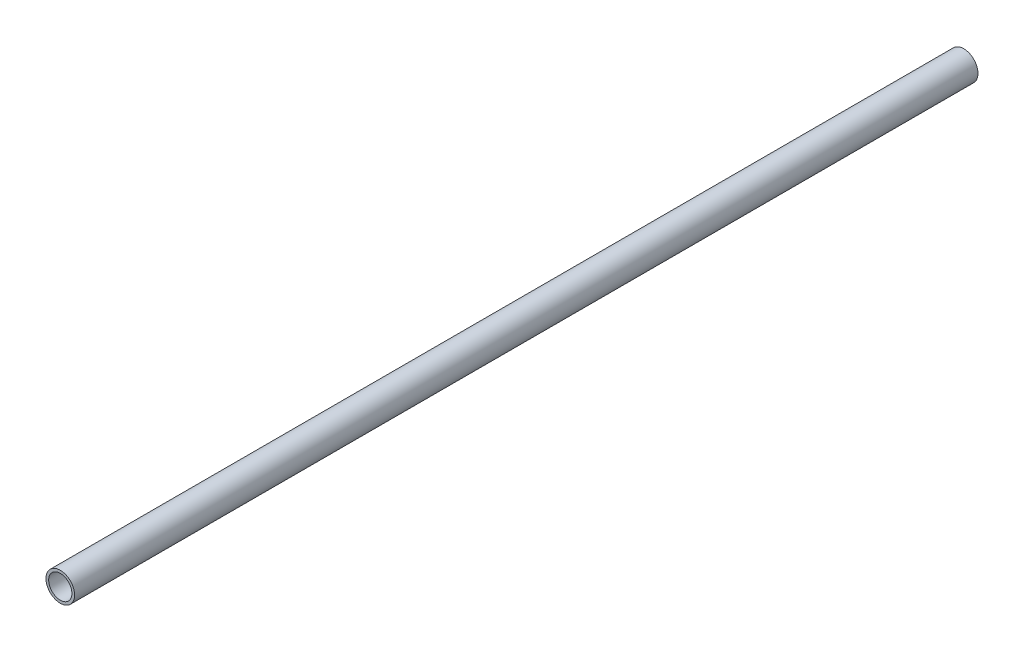
SolidWorks part; units mm, degrees
ref_plane "Alzado" through (0, 0, 0) normal (0, 0, 1) x (1, 0, 0)
ref_plane "Planta" through (0, 0, 0) normal (0, 1, 0) x (1, 0, 0)
ref_plane "Vista lateral" through (0, 0, 0) normal (1, 0, 0) x (0, 0, -1)
sketch "Croquis1" plane through (0, 0, 0) normal (0, 0, 1) x (1, 0, 0)
  circle A0 centre (0, 0) radius 16
  dimension "D1" = 32
extrude "Extruir1" add sketch "Croquis1" along normal mid plane 1010
shell "Vaciado1" thickness 3
